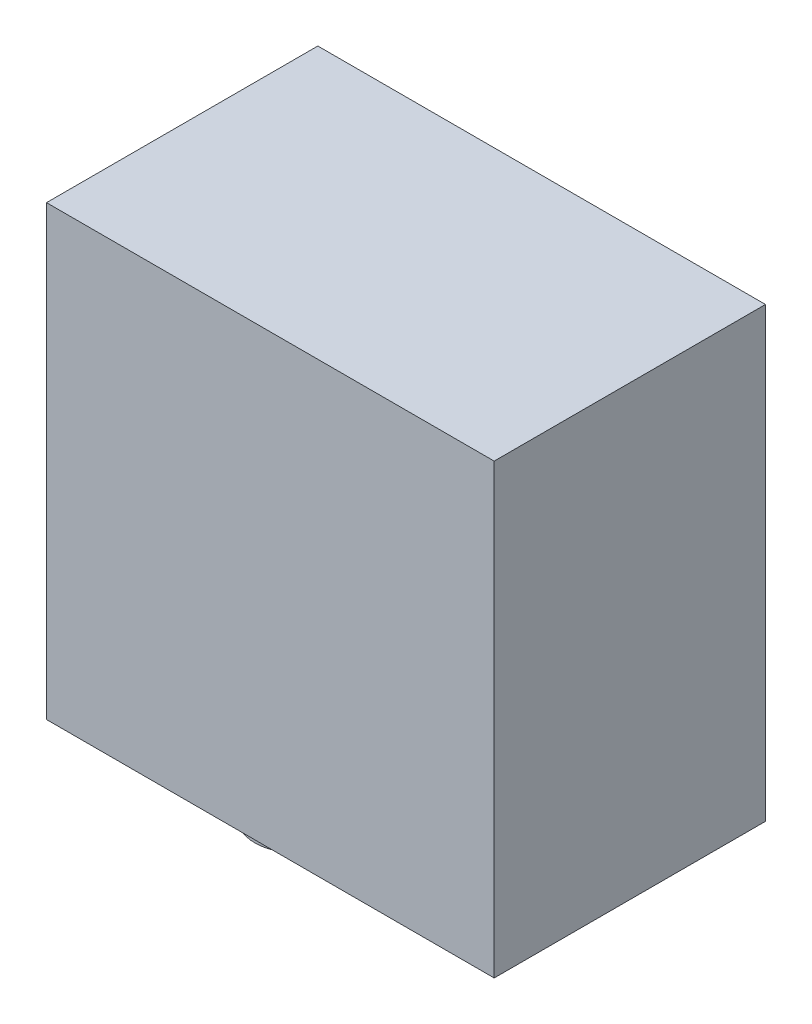
SolidWorks part; units mm, degrees
ref_plane "Front Plane" through (0, 0, 0) normal (0, 0, 1) x (1, 0, 0)
ref_plane "Top Plane" through (0, 0, 0) normal (0, 1, 0) x (1, 0, 0)
ref_plane "Right Plane" through (0, 0, 0) normal (1, 0, 0) x (0, 0, -1)
sketch "Sketch1" plane through (0, 0, 0) normal (0, 0, 1) x (1, 0, 0)
  line L1 (-16.5, 16.5) -> (16.5, 16.5)
  line L2 (-16.5, 16.5) -> (-16.5, -16.5)
  line L3 (-16.5, -16.5) -> (16.5, -16.5)
  line L4 (16.5, 16.5) -> (16.5, -16.5)
  line L5 (-16.5, 16.5) -> (16.5, -16.5) construction
  line L6 (-16.5, -16.5) -> (16.5, 16.5) construction
  point P0 (0, 0)
  dimension "D1" = 33
  dimension "D2" = 33
extrude "Boss-Extrude1" add sketch "Sketch1" along normal blind 20
sketch "Sketch2" plane through (0, -16.5, 0) normal (0, -1, 0) x (1, 0, 0)
  circle A0 centre (-10.9342, 7.1798) radius 3.0186
extrude "Boss-Extrude2" add sketch "Sketch2" along normal blind 10
